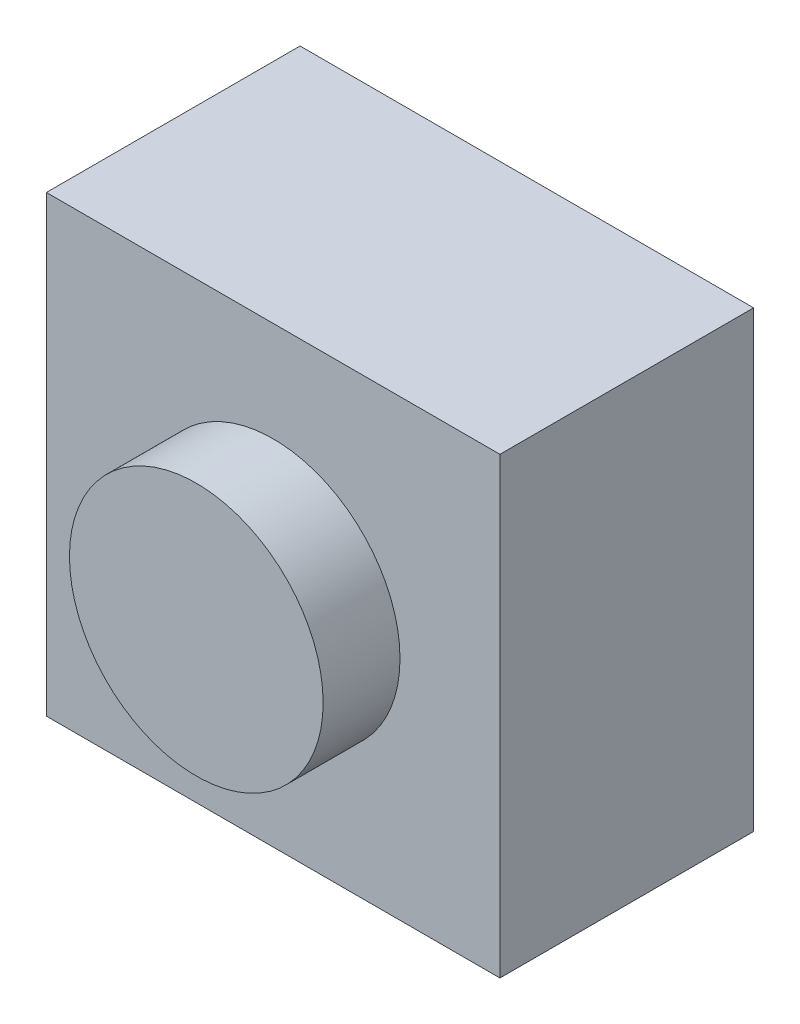
SolidWorks part; units mm, degrees
ref_plane "Plano frontal" through (0, 0, 0) normal (0, 0, 1) x (1, 0, 0)
ref_plane "Plano superior" through (0, 0, 0) normal (0, 1, 0) x (1, 0, 0)
ref_plane "Plano direito" through (0, 0, 0) normal (1, 0, 0) x (0, 0, -1)
sketch "Esboço1" plane through (0, 0, 0) normal (0, 0, 1) x (1, 0, 0)
  line L1 (-2.95, 2.95) -> (2.95, 2.95)
  line L2 (-2.95, 2.95) -> (-2.95, -2.95)
  line L3 (-2.95, -2.95) -> (2.95, -2.95)
  line L4 (2.95, 2.95) -> (2.95, -2.95)
  line L5 (-2.95, 2.95) -> (2.95, -2.95) construction
  line L6 (-2.95, -2.95) -> (2.95, 2.95) construction
  point P0 (0, 0)
  dimension "D1" = 5.9
extrude "Ressalto-extrusão1" add sketch "Esboço1" along normal blind 3.3
sketch "Esboço2" plane through (0, 0, 3.3) normal (0, 0, 1) x (1, 0, 0)
  circle A0 centre (0, 0) radius 1.65
  dimension "D1" = 3.3
extrude "Ressalto-extrusão2" add sketch "Esboço2" along normal blind 1
